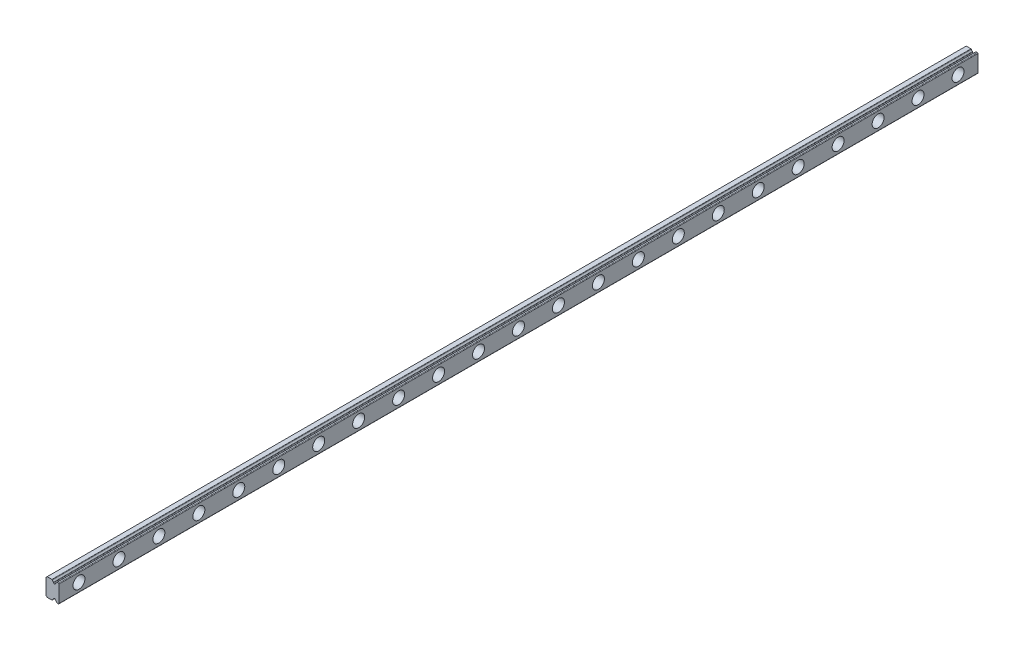
SolidWorks part; units mm, degrees
material "AISI 304"
ref_plane "前视基准面" through (0, 0, 0) normal (0, 0, 1) x (1, 0, 0)
ref_plane "上视基准面" through (0, 0, 0) normal (0, 1, 0) x (1, 0, 0)
ref_plane "右视基准面" through (0, 0, 0) normal (1, 0, 0) x (0, 0, -1)
sketch "草图1" plane through (0, 0, 0) normal (0, 0, 1) x (1, 0, 0)
  line L0 (0, 8.4) -> (0.6, 9)
  line L1 (0.6, 0) -> (2.9423, 0)
  line L2 (0, 0.6) -> (0, 8.4)
  line L3 (0.6, 9) -> (2.9423, 9)
  line L4 (6.5, 0.3) -> (6.5, 8.7)
  line L5 (0, 0.6) -> (0.6, 0)
  line L6 (4.25, 9) -> (4.25, 8) construction
  line L7 (4.25, 9) -> (4.25, 9.3) construction
  line L8 (3.85, 8) -> (3.85, 8.0351)
  line L9 (4.65, 8) -> (4.65, 8.0351)
  line L10 (5.5577, 9) -> (6.2, 9)
  line L11 (6.5, 4.5) -> (0, 4.5) construction
  line L12 (3.85, 8) -> (3.85, 8.0351)
  line L13 (4.65, 8) -> (4.65, 8.0351)
  line L14 (4.25, 0) -> (4.25, -0.3) construction
  line L15 (4.25, 0) -> (4.25, 1) construction
  line L16 (4.65, 1) -> (4.65, 0.9649)
  line L17 (3.85, 1) -> (3.85, 0.9649)
  line L18 (4.65, 1) -> (4.65, 0.9649)
  line L19 (3.85, 1) -> (3.85, 0.9649)
  line L20 (5.5577, 0) -> (6.2, 0)
  arc A0 (3.85, 8) -> (4.65, 8) centre (4.25, 8) ccw
  arc A1 (3.1291, 8.8714) -> (3.7357, 8.2158) centre (4.25, 9.3) ccw
  arc A2 (4.7643, 8.2158) -> (5.3709, 8.8714) centre (4.25, 9.3) ccw
  arc A3 (5.3709, 8.8714) -> (5.5577, 9) centre (5.5577, 8.8) cw
  arc A4 (4.65, 8.0351) -> (4.7643, 8.2158) centre (4.85, 8.0351) cw
  arc A5 (3.85, 8.0351) -> (3.7357, 8.2158) centre (3.65, 8.0351) ccw
  arc A6 (3.1291, 8.8714) -> (2.9423, 9) centre (2.9423, 8.8) ccw
  arc A7 (3.1291, 8.8714) -> (2.9423, 9) centre (2.9423, 8.8) ccw
  arc A8 (5.3709, 8.8714) -> (5.5577, 9) centre (5.5577, 8.8) cw
  arc A9 (4.65, 8.0351) -> (4.7643, 8.2158) centre (4.85, 8.0351) cw
  arc A10 (3.85, 8.0351) -> (3.7357, 8.2158) centre (3.65, 8.0351) ccw
  arc A11 (3.7357, 8.2158) -> (3.1291, 8.8714) centre (4.25, 9.3) cw
  arc A12 (5.3709, 8.8714) -> (4.7643, 8.2158) centre (4.25, 9.3) cw
  arc A13 (5.3709, 0.1286) -> (5.5577, 0) centre (5.5577, 0.2) ccw
  arc A14 (3.1291, 0.1286) -> (2.9423, 0) centre (2.9423, 0.2) cw
  arc A15 (5.3709, 0.1286) -> (4.7643, 0.7842) centre (4.25, -0.3) ccw
  arc A16 (3.7357, 0.7842) -> (3.1291, 0.1286) centre (4.25, -0.3) ccw
  arc A17 (3.85, 0.9649) -> (3.7357, 0.7842) centre (3.65, 0.9649) cw
  arc A18 (4.65, 0.9649) -> (4.7643, 0.7842) centre (4.85, 0.9649) ccw
  arc A19 (3.85, 0.9649) -> (3.7357, 0.7842) centre (3.65, 0.9649) cw
  arc A20 (4.65, 0.9649) -> (4.7643, 0.7842) centre (4.85, 0.9649) ccw
  arc A21 (4.7643, 0.7842) -> (5.3709, 0.1286) centre (4.25, -0.3) cw
  arc A22 (3.1291, 0.1286) -> (3.7357, 0.7842) centre (4.25, -0.3) cw
  arc A23 (3.85, 1) -> (4.65, 1) centre (4.25, 1) cw
  arc A24 (6.2, 0) -> (6.5, 0.3) centre (6.2, 0.3) ccw
  arc A25 (6.2, 9) -> (6.5, 8.7) centre (6.2, 8.7) cw
  point P0 (0, 0)
  point P2 (0, 9)
  point P24 (5.4119, 9)
  point P27 (4.65, 8.1686)
  point P49 (4.65, 0.8314)
  point P50 (5.4119, 0)
  point P53 (6.5, 0)
  dimension "D3" = 1
  dimension "D7" = 0.8
  dimension "D9" = 2.4
  dimension "D10" = 0.2
  dimension "D11" = 0.3
  dimension "D1" = 6.5
  dimension "D2" = 9
  dimension "D4" = 2.25
  dimension "D8" = 0.3
extrude "凸台-拉伸1" add sketch "草图1" along normal blind 400 contours A25 L10 A3 A2 A4 L9 A0 L8 A5 A1 A6 L3 L0 L2 L5 L1 A14 A16 A17 L17 A23 L16 A18 A15 A13 L20 A24 L4
sketch "草图2" plane through (6.5, 0, 0) normal (1, 0, 0) x (0, 0, -1)
  line L0 (-400, 4.5) -> (-390, 4.5) construction
  line L1 (-400, 0.3) -> (-400, 8.7) construction
  line L2 (-390, 4.5) -> (-10, 4.5) construction
  line L3 (-10, 4.5) -> (0, 4.5) construction
  line L4 (0, 0.3) -> (0, 8.7) construction
  line L5 (-10, 4.5) -> (-30, 4.5) construction
  circle A0 centre (-10, 4.5) radius 3
  circle A1 centre (-30, 4.5) radius 3
  circle A2 centre (-50, 4.5) radius 3
  circle A3 centre (-70, 4.5) radius 3
  circle A4 centre (-90, 4.5) radius 3
  circle A5 centre (-110, 4.5) radius 3
  circle A6 centre (-130, 4.5) radius 3
  circle A7 centre (-150, 4.5) radius 3
  circle A8 centre (-170, 4.5) radius 3
  circle A9 centre (-190, 4.5) radius 3
  circle A10 centre (-210, 4.5) radius 3
  circle A11 centre (-230, 4.5) radius 3
  circle A12 centre (-250, 4.5) radius 3
  circle A13 centre (-270, 4.5) radius 3
  circle A14 centre (-290, 4.5) radius 3
  circle A15 centre (-310, 4.5) radius 3
  circle A16 centre (-330, 4.5) radius 3
  circle A17 centre (-350, 4.5) radius 3
  circle A18 centre (-370, 4.5) radius 3
  circle A19 centre (-390, 4.5) radius 3
  circle A20 centre (-410, 4.5) radius 3
  circle A21 centre (-430, 4.5) radius 3
  circle A22 centre (-450, 4.5) radius 3
  circle A23 centre (-470, 4.5) radius 3
  circle A24 centre (-490, 4.5) radius 3
  circle A25 centre (-510, 4.5) radius 3
  circle A26 centre (-530, 4.5) radius 3
  circle A27 centre (-550, 4.5) radius 3
  circle A28 centre (-570, 4.5) radius 3
  circle A29 centre (-590, 4.5) radius 3
  circle A30 centre (-610, 4.5) radius 3
  circle A31 centre (-630, 4.5) radius 3
  circle A32 centre (-650, 4.5) radius 3
  circle A33 centre (-670, 4.5) radius 3
  circle A34 centre (-690, 4.5) radius 3
  circle A35 centre (-710, 4.5) radius 3
  circle A36 centre (-730, 4.5) radius 3
  circle A37 centre (-750, 4.5) radius 3
  circle A38 centre (-770, 4.5) radius 3
  circle A39 centre (-790, 4.5) radius 3
  circle A40 centre (-810, 4.5) radius 3
  circle A41 centre (-830, 4.5) radius 3
  circle A42 centre (-850, 4.5) radius 3
  circle A43 centre (-870, 4.5) radius 3
  circle A44 centre (-890, 4.5) radius 3
  circle A45 centre (-910, 4.5) radius 3
  circle A46 centre (-930, 4.5) radius 3
  circle A47 centre (-950, 4.5) radius 3
  circle A48 centre (-970, 4.5) radius 3
  circle A49 centre (-990, 4.5) radius 3
  circle A50 centre (-1010, 4.5) radius 3
  circle A51 centre (-1030, 4.5) radius 3
  circle A52 centre (-1050, 4.5) radius 3
  circle A53 centre (-1070, 4.5) radius 3
  circle A54 centre (-1090, 4.5) radius 3
  circle A55 centre (-1110, 4.5) radius 3
  circle A56 centre (-1130, 4.5) radius 3
  circle A57 centre (-1150, 4.5) radius 3
  circle A58 centre (-1170, 4.5) radius 3
  circle A59 centre (-1190, 4.5) radius 3
  circle A60 centre (-1210, 4.5) radius 3
  circle A61 centre (-1230, 4.5) radius 3
  circle A62 centre (-1250, 4.5) radius 3
  circle A63 centre (-1270, 4.5) radius 3
  circle A64 centre (-1290, 4.5) radius 3
  circle A65 centre (-1310, 4.5) radius 3
  circle A66 centre (-1330, 4.5) radius 3
  circle A67 centre (-1350, 4.5) radius 3
  circle A68 centre (-1370, 4.5) radius 3
  circle A69 centre (-1390, 4.5) radius 3
  circle A70 centre (-1410, 4.5) radius 3
  circle A71 centre (-1430, 4.5) radius 3
  circle A72 centre (-1450, 4.5) radius 3
  circle A73 centre (-1470, 4.5) radius 3
  circle A74 centre (-1490, 4.5) radius 3
  circle A75 centre (-1510, 4.5) radius 3
  circle A76 centre (-1530, 4.5) radius 3
  circle A77 centre (-1550, 4.5) radius 3
  circle A78 centre (-1570, 4.5) radius 3
  circle A79 centre (-1590, 4.5) radius 3
  circle A80 centre (-1610, 4.5) radius 3
  circle A81 centre (-1630, 4.5) radius 3
  circle A82 centre (-1650, 4.5) radius 3
  circle A83 centre (-1670, 4.5) radius 3
  circle A84 centre (-1690, 4.5) radius 3
  circle A85 centre (-1710, 4.5) radius 3
  circle A86 centre (-1730, 4.5) radius 3
  circle A87 centre (-1750, 4.5) radius 3
  circle A88 centre (-1770, 4.5) radius 3
  circle A89 centre (-1790, 4.5) radius 3
  circle A90 centre (-1810, 4.5) radius 3
  circle A91 centre (-1830, 4.5) radius 3
  circle A92 centre (-1850, 4.5) radius 3
  circle A93 centre (-1870, 4.5) radius 3
  circle A94 centre (-1890, 4.5) radius 3
  circle A95 centre (-1910, 4.5) radius 3
  circle A96 centre (-1930, 4.5) radius 3
  circle A97 centre (-1950, 4.5) radius 3
  circle A98 centre (-1970, 4.5) radius 3
  circle A99 centre (-1990, 4.5) radius 3
  circle A100 centre (-2010, 4.5) radius 3
  circle A101 centre (-2030, 4.5) radius 3
  circle A102 centre (-2050, 4.5) radius 3
  circle A103 centre (-2070, 4.5) radius 3
  circle A104 centre (-2090, 4.5) radius 3
  circle A105 centre (-2110, 4.5) radius 3
  circle A106 centre (-2130, 4.5) radius 3
  circle A107 centre (-2150, 4.5) radius 3
  circle A108 centre (-2170, 4.5) radius 3
  circle A109 centre (-2190, 4.5) radius 3
  circle A110 centre (-2210, 4.5) radius 3
  circle A111 centre (-2230, 4.5) radius 3
  circle A112 centre (-2250, 4.5) radius 3
  circle A113 centre (-2270, 4.5) radius 3
  circle A114 centre (-2290, 4.5) radius 3
  circle A115 centre (-2310, 4.5) radius 3
  circle A116 centre (-2330, 4.5) radius 3
  circle A117 centre (-2350, 4.5) radius 3
  circle A118 centre (-2370, 4.5) radius 3
  circle A119 centre (-2390, 4.5) radius 3
  circle A120 centre (-2410, 4.5) radius 3
  circle A121 centre (-2430, 4.5) radius 3
  circle A122 centre (-2450, 4.5) radius 3
  circle A123 centre (-2470, 4.5) radius 3
  dimension "D2" = 6
  dimension "D1" = 10
  dimension "D4" = 20
  dimension "D3" = 25
  dimension "D5" = 100
extrude "切除-拉伸1" cut sketch "草图2" against normal blind 4.5
sketch "草图3" plane through (2, 0, 0) normal (1, 0, 0) x (0, 0, -1)
  line L0 (-10, 4.5) -> (-30, 4.5) construction
  circle A0 centre (-10, 4.5) radius 1.75
  circle A1 centre (-30, 4.5) radius 1.75
  circle A2 centre (-50, 4.5) radius 1.75
  circle A3 centre (-70, 4.5) radius 1.75
  circle A4 centre (-90, 4.5) radius 1.75
  circle A5 centre (-110, 4.5) radius 1.75
  circle A6 centre (-130, 4.5) radius 1.75
  circle A7 centre (-150, 4.5) radius 1.75
  circle A8 centre (-170, 4.5) radius 1.75
  circle A9 centre (-190, 4.5) radius 1.75
  circle A10 centre (-210, 4.5) radius 1.75
  circle A11 centre (-230, 4.5) radius 1.75
  circle A12 centre (-250, 4.5) radius 1.75
  circle A13 centre (-270, 4.5) radius 1.75
  circle A14 centre (-290, 4.5) radius 1.75
  circle A15 centre (-310, 4.5) radius 1.75
  circle A16 centre (-330, 4.5) radius 1.75
  circle A17 centre (-350, 4.5) radius 1.75
  circle A18 centre (-370, 4.5) radius 1.75
  circle A19 centre (-390, 4.5) radius 1.75
  circle A20 centre (-410, 4.5) radius 1.75
  circle A21 centre (-430, 4.5) radius 1.75
  circle A22 centre (-450, 4.5) radius 1.75
  circle A23 centre (-470, 4.5) radius 1.75
  circle A24 centre (-490, 4.5) radius 1.75
  circle A25 centre (-510, 4.5) radius 1.75
  circle A26 centre (-530, 4.5) radius 1.75
  circle A27 centre (-550, 4.5) radius 1.75
  circle A28 centre (-570, 4.5) radius 1.75
  circle A29 centre (-590, 4.5) radius 1.75
  circle A30 centre (-610, 4.5) radius 1.75
  circle A31 centre (-630, 4.5) radius 1.75
  circle A32 centre (-650, 4.5) radius 1.75
  circle A33 centre (-670, 4.5) radius 1.75
  circle A34 centre (-690, 4.5) radius 1.75
  circle A35 centre (-710, 4.5) radius 1.75
  circle A36 centre (-730, 4.5) radius 1.75
  circle A37 centre (-750, 4.5) radius 1.75
  circle A38 centre (-770, 4.5) radius 1.75
  circle A39 centre (-790, 4.5) radius 1.75
  circle A40 centre (-810, 4.5) radius 1.75
  circle A41 centre (-830, 4.5) radius 1.75
  circle A42 centre (-850, 4.5) radius 1.75
  circle A43 centre (-870, 4.5) radius 1.75
  circle A44 centre (-890, 4.5) radius 1.75
  circle A45 centre (-910, 4.5) radius 1.75
  circle A46 centre (-930, 4.5) radius 1.75
  circle A47 centre (-950, 4.5) radius 1.75
  circle A48 centre (-970, 4.5) radius 1.75
  circle A49 centre (-990, 4.5) radius 1.75
  circle A50 centre (-1010, 4.5) radius 1.75
  circle A51 centre (-1030, 4.5) radius 1.75
  circle A52 centre (-1050, 4.5) radius 1.75
  circle A53 centre (-1070, 4.5) radius 1.75
  dimension "D1" = 3.5
  dimension "D3" = 20
  dimension "D2" = 25
  dimension "D4" = 30
extrude "切除-拉伸2" cut sketch "草图3" against normal through all
sketch "草图4" plane through (0, 0, 400) normal (0, 0, 1) x (1, 0, 0)
  line L12 (6.2, 9) -> (5.5577, 9)
  line L13 (4.65, 8.0351) -> (4.65, 8)
  line L14 (3.85, 8) -> (3.85, 8.0351)
  line L15 (2.9423, 9) -> (0.6, 9)
  line L16 (0.6, 9) -> (0, 8.4)
  line L17 (0, 8.4) -> (0, 0.6)
  line L18 (0, 0.6) -> (0.6, 0)
  line L19 (0.6, 0) -> (2.9423, 0)
  line L20 (3.85, 0.9649) -> (3.85, 1)
  line L21 (4.65, 1) -> (4.65, 0.9649)
  line L22 (5.5577, 0) -> (6.2, 0)
  line L23 (6.5, 0.3) -> (6.5, 8.7)
  line L24 (6.2, 9) -> (5.5577, 9)
  line L25 (4.65, 8.0351) -> (4.65, 8)
  line L26 (3.85, 8) -> (3.85, 8.0351)
  line L27 (2.9423, 9) -> (0.6, 9)
  line L28 (0.6, 9) -> (0, 8.4)
  line L29 (0, 8.4) -> (0, 0.6)
  line L30 (0, 0.6) -> (0.6, 0)
  line L31 (0.6, 0) -> (2.9423, 0)
  line L32 (3.85, 0.9649) -> (3.85, 1)
  line L33 (4.65, 1) -> (4.65, 0.9649)
  line L34 (5.5577, 0) -> (6.2, 0)
  line L35 (6.5, 0.3) -> (6.5, 8.7)
  arc A16 (6.5, 8.7) -> (6.2, 9) centre (6.2, 8.7) ccw
  arc A17 (5.5577, 9) -> (5.3709, 8.8714) centre (5.5577, 8.8) ccw
  arc A18 (4.7643, 8.2158) -> (5.3709, 8.8714) centre (4.25, 9.3) ccw
  arc A19 (4.7643, 8.2158) -> (4.65, 8.0351) centre (4.85, 8.0351) ccw
  arc A20 (3.85, 8) -> (4.65, 8) centre (4.25, 8) ccw
  arc A21 (3.85, 8.0351) -> (3.7357, 8.2158) centre (3.65, 8.0351) ccw
  arc A22 (3.1291, 8.8714) -> (3.7357, 8.2158) centre (4.25, 9.3) ccw
  arc A23 (3.1291, 8.8714) -> (2.9423, 9) centre (2.9423, 8.8) ccw
  arc A24 (2.9423, 0) -> (3.1291, 0.1286) centre (2.9423, 0.2) ccw
  arc A25 (3.7357, 0.7842) -> (3.1291, 0.1286) centre (4.25, -0.3) ccw
  arc A26 (3.7357, 0.7842) -> (3.85, 0.9649) centre (3.65, 0.9649) ccw
  arc A27 (4.65, 1) -> (3.85, 1) centre (4.25, 1) ccw
  arc A28 (4.65, 0.9649) -> (4.7643, 0.7842) centre (4.85, 0.9649) ccw
  arc A29 (5.3709, 0.1286) -> (4.7643, 0.7842) centre (4.25, -0.3) ccw
  arc A30 (5.3709, 0.1286) -> (5.5577, 0) centre (5.5577, 0.2) ccw
  arc A31 (6.2, 0) -> (6.5, 0.3) centre (6.2, 0.3) ccw
  arc A32 (6.5, 8.7) -> (6.2, 9) centre (6.2, 8.7) ccw
  arc A33 (5.5577, 9) -> (5.3709, 8.8714) centre (5.5577, 8.8) ccw
  arc A34 (4.7643, 8.2158) -> (5.3709, 8.8714) centre (4.25, 9.3) ccw
  arc A35 (4.7643, 8.2158) -> (4.65, 8.0351) centre (4.85, 8.0351) ccw
  arc A36 (3.85, 8) -> (4.65, 8) centre (4.25, 8) ccw
  arc A37 (3.85, 8.0351) -> (3.7357, 8.2158) centre (3.65, 8.0351) ccw
  arc A38 (3.1291, 8.8714) -> (3.7357, 8.2158) centre (4.25, 9.3) ccw
  arc A39 (3.1291, 8.8714) -> (2.9423, 9) centre (2.9423, 8.8) ccw
  arc A40 (2.9423, 0) -> (3.1291, 0.1286) centre (2.9423, 0.2) ccw
  arc A41 (3.7357, 0.7842) -> (3.1291, 0.1286) centre (4.25, -0.3) ccw
  arc A42 (3.7357, 0.7842) -> (3.85, 0.9649) centre (3.65, 0.9649) ccw
  arc A43 (4.65, 1) -> (3.85, 1) centre (4.25, 1) ccw
  arc A44 (4.65, 0.9649) -> (4.7643, 0.7842) centre (4.85, 0.9649) ccw
  arc A45 (5.3709, 0.1286) -> (4.7643, 0.7842) centre (4.25, -0.3) ccw
  arc A46 (5.3709, 0.1286) -> (5.5577, 0) centre (5.5577, 0.2) ccw
  arc A47 (6.2, 0) -> (6.5, 0.3) centre (6.2, 0.3) ccw
  dimension "D1" = 0
sketch "草图5" plane through (0, 0, 0) normal (0, 0, -1) x (-1, 0, 0)
  line L12 (-6.5, 8.7) -> (-6.5, 0.3)
  line L13 (-6.2, 0) -> (-5.5577, 0)
  line L14 (-4.65, 0.9649) -> (-4.65, 1)
  line L15 (-3.85, 1) -> (-3.85, 0.9649)
  line L16 (-2.9423, 0) -> (-0.6, 0)
  line L17 (-0.6, 0) -> (0, 0.6)
  line L18 (0, 0.6) -> (0, 8.4)
  line L19 (0, 8.4) -> (-0.6, 9)
  line L20 (-0.6, 9) -> (-2.9423, 9)
  line L21 (-3.85, 8.0351) -> (-3.85, 8)
  line L22 (-4.65, 8) -> (-4.65, 8.0351)
  line L23 (-5.5577, 9) -> (-6.2, 9)
  line L24 (-6.5, 8.7) -> (-6.5, 0.3)
  line L25 (-6.2, 0) -> (-5.5577, 0)
  line L26 (-4.65, 0.9649) -> (-4.65, 1)
  line L27 (-3.85, 1) -> (-3.85, 0.9649)
  line L28 (-2.9423, 0) -> (-0.6, 0)
  line L29 (-0.6, 0) -> (0, 0.6)
  line L30 (0, 0.6) -> (0, 8.4)
  line L31 (0, 8.4) -> (-0.6, 9)
  line L32 (-0.6, 9) -> (-2.9423, 9)
  line L33 (-3.85, 8.0351) -> (-3.85, 8)
  line L34 (-4.65, 8) -> (-4.65, 8.0351)
  line L35 (-5.5577, 9) -> (-6.2, 9)
  arc A16 (-6.2, 9) -> (-6.5, 8.7) centre (-6.2, 8.7) ccw
  arc A17 (-6.5, 0.3) -> (-6.2, 0) centre (-6.2, 0.3) ccw
  arc A18 (-5.5577, 0) -> (-5.3709, 0.1286) centre (-5.5577, 0.2) ccw
  arc A19 (-4.7643, 0.7842) -> (-5.3709, 0.1286) centre (-4.25, -0.3) ccw
  arc A20 (-4.7643, 0.7842) -> (-4.65, 0.9649) centre (-4.85, 0.9649) ccw
  arc A21 (-3.85, 1) -> (-4.65, 1) centre (-4.25, 1) ccw
  arc A22 (-3.85, 0.9649) -> (-3.7357, 0.7842) centre (-3.65, 0.9649) ccw
  arc A23 (-3.1291, 0.1286) -> (-3.7357, 0.7842) centre (-4.25, -0.3) ccw
  arc A24 (-3.1291, 0.1286) -> (-2.9423, 0) centre (-2.9423, 0.2) ccw
  arc A25 (-2.9423, 9) -> (-3.1291, 8.8714) centre (-2.9423, 8.8) ccw
  arc A26 (-3.7357, 8.2158) -> (-3.1291, 8.8714) centre (-4.25, 9.3) ccw
  arc A27 (-3.7357, 8.2158) -> (-3.85, 8.0351) centre (-3.65, 8.0351) ccw
  arc A28 (-4.65, 8) -> (-3.85, 8) centre (-4.25, 8) ccw
  arc A29 (-4.65, 8.0351) -> (-4.7643, 8.2158) centre (-4.85, 8.0351) ccw
  arc A30 (-5.3709, 8.8714) -> (-4.7643, 8.2158) centre (-4.25, 9.3) ccw
  arc A31 (-5.3709, 8.8714) -> (-5.5577, 9) centre (-5.5577, 8.8) ccw
  arc A32 (-6.2, 9) -> (-6.5, 8.7) centre (-6.2, 8.7) ccw
  arc A33 (-6.5, 0.3) -> (-6.2, 0) centre (-6.2, 0.3) ccw
  arc A34 (-5.5577, 0) -> (-5.3709, 0.1286) centre (-5.5577, 0.2) ccw
  arc A35 (-4.7643, 0.7842) -> (-5.3709, 0.1286) centre (-4.25, -0.3) ccw
  arc A36 (-4.7643, 0.7842) -> (-4.65, 0.9649) centre (-4.85, 0.9649) ccw
  arc A37 (-3.85, 1) -> (-4.65, 1) centre (-4.25, 1) ccw
  arc A38 (-3.85, 0.9649) -> (-3.7357, 0.7842) centre (-3.65, 0.9649) ccw
  arc A39 (-3.1291, 0.1286) -> (-3.7357, 0.7842) centre (-4.25, -0.3) ccw
  arc A40 (-3.1291, 0.1286) -> (-2.9423, 0) centre (-2.9423, 0.2) ccw
  arc A41 (-2.9423, 9) -> (-3.1291, 8.8714) centre (-2.9423, 8.8) ccw
  arc A42 (-3.7357, 8.2158) -> (-3.1291, 8.8714) centre (-4.25, 9.3) ccw
  arc A43 (-3.7357, 8.2158) -> (-3.85, 8.0351) centre (-3.65, 8.0351) ccw
  arc A44 (-4.65, 8) -> (-3.85, 8) centre (-4.25, 8) ccw
  arc A45 (-4.65, 8.0351) -> (-4.7643, 8.2158) centre (-4.85, 8.0351) ccw
  arc A46 (-5.3709, 8.8714) -> (-4.7643, 8.2158) centre (-4.25, 9.3) ccw
  arc A47 (-5.3709, 8.8714) -> (-5.5577, 9) centre (-5.5577, 8.8) ccw
  dimension "D1" = 0
extrude "切除-拉伸4" cut sketch "草图5" against normal blind 80
sketch "草图6" plane through (0, 0, 400) normal (0, 0, 1) x (1, 0, 0)
  line L12 (6.2, 9) -> (5.5577, 9)
  line L13 (4.65, 8.0351) -> (4.65, 8)
  line L14 (3.85, 8) -> (3.85, 8.0351)
  line L15 (2.9423, 9) -> (0.6, 9)
  line L16 (0.6, 9) -> (0, 8.4)
  line L17 (0, 8.4) -> (0, 0.6)
  line L18 (0, 0.6) -> (0.6, 0)
  line L19 (0.6, 0) -> (2.9423, 0)
  line L20 (3.85, 0.9649) -> (3.85, 1)
  line L21 (4.65, 1) -> (4.65, 0.9649)
  line L22 (5.5577, 0) -> (6.2, 0)
  line L23 (6.5, 0.3) -> (6.5, 8.7)
  line L24 (6.2, 9) -> (5.5577, 9)
  line L25 (4.65, 8.0351) -> (4.65, 8)
  line L26 (3.85, 8) -> (3.85, 8.0351)
  line L27 (2.9423, 9) -> (0.6, 9)
  line L28 (0.6, 9) -> (0, 8.4)
  line L29 (0, 8.4) -> (0, 0.6)
  line L30 (0, 0.6) -> (0.6, 0)
  line L31 (0.6, 0) -> (2.9423, 0)
  line L32 (3.85, 0.9649) -> (3.85, 1)
  line L33 (4.65, 1) -> (4.65, 0.9649)
  line L34 (5.5577, 0) -> (6.2, 0)
  line L35 (6.5, 0.3) -> (6.5, 8.7)
  arc A16 (6.5, 8.7) -> (6.2, 9) centre (6.2, 8.7) ccw
  arc A17 (5.5577, 9) -> (5.3709, 8.8714) centre (5.5577, 8.8) ccw
  arc A18 (4.7643, 8.2158) -> (5.3709, 8.8714) centre (4.25, 9.3) ccw
  arc A19 (4.7643, 8.2158) -> (4.65, 8.0351) centre (4.85, 8.0351) ccw
  arc A20 (3.85, 8) -> (4.65, 8) centre (4.25, 8) ccw
  arc A21 (3.85, 8.0351) -> (3.7357, 8.2158) centre (3.65, 8.0351) ccw
  arc A22 (3.1291, 8.8714) -> (3.7357, 8.2158) centre (4.25, 9.3) ccw
  arc A23 (3.1291, 8.8714) -> (2.9423, 9) centre (2.9423, 8.8) ccw
  arc A24 (2.9423, 0) -> (3.1291, 0.1286) centre (2.9423, 0.2) ccw
  arc A25 (3.7357, 0.7842) -> (3.1291, 0.1286) centre (4.25, -0.3) ccw
  arc A26 (3.7357, 0.7842) -> (3.85, 0.9649) centre (3.65, 0.9649) ccw
  arc A27 (4.65, 1) -> (3.85, 1) centre (4.25, 1) ccw
  arc A28 (4.65, 0.9649) -> (4.7643, 0.7842) centre (4.85, 0.9649) ccw
  arc A29 (5.3709, 0.1286) -> (4.7643, 0.7842) centre (4.25, -0.3) ccw
  arc A30 (5.3709, 0.1286) -> (5.5577, 0) centre (5.5577, 0.2) ccw
  arc A31 (6.2, 0) -> (6.5, 0.3) centre (6.2, 0.3) ccw
  arc A32 (6.5, 8.7) -> (6.2, 9) centre (6.2, 8.7) ccw
  arc A33 (5.5577, 9) -> (5.3709, 8.8714) centre (5.5577, 8.8) ccw
  arc A34 (4.7643, 8.2158) -> (5.3709, 8.8714) centre (4.25, 9.3) ccw
  arc A35 (4.7643, 8.2158) -> (4.65, 8.0351) centre (4.85, 8.0351) ccw
  arc A36 (3.85, 8) -> (4.65, 8) centre (4.25, 8) ccw
  arc A37 (3.85, 8.0351) -> (3.7357, 8.2158) centre (3.65, 8.0351) ccw
  arc A38 (3.1291, 8.8714) -> (3.7357, 8.2158) centre (4.25, 9.3) ccw
  arc A39 (3.1291, 8.8714) -> (2.9423, 9) centre (2.9423, 8.8) ccw
  arc A40 (2.9423, 0) -> (3.1291, 0.1286) centre (2.9423, 0.2) ccw
  arc A41 (3.7357, 0.7842) -> (3.1291, 0.1286) centre (4.25, -0.3) ccw
  arc A42 (3.7357, 0.7842) -> (3.85, 0.9649) centre (3.65, 0.9649) ccw
  arc A43 (4.65, 1) -> (3.85, 1) centre (4.25, 1) ccw
  arc A44 (4.65, 0.9649) -> (4.7643, 0.7842) centre (4.85, 0.9649) ccw
  arc A45 (5.3709, 0.1286) -> (4.7643, 0.7842) centre (4.25, -0.3) ccw
  arc A46 (5.3709, 0.1286) -> (5.5577, 0) centre (5.5577, 0.2) ccw
  arc A47 (6.2, 0) -> (6.5, 0.3) centre (6.2, 0.3) ccw
  dimension "D1" = 0
extrude "凸台-拉伸2" add sketch "草图6" along normal blind 200
sketch "草图7" plane through (0, 0, 0) normal (-1, 0, 0) x (0, 0, 1)
  circle A0 centre (390, 4.5) radius 1.75 construction
  circle A1 centre (390, 4.5) radius 1.75
  circle A2 centre (410, 4.5) radius 1.75
  circle A3 centre (430, 4.5) radius 1.75
  circle A4 centre (450, 4.5) radius 1.75
  circle A5 centre (470, 4.5) radius 1.75
  circle A6 centre (490, 4.5) radius 1.75
  circle A7 centre (510, 4.5) radius 1.75
  circle A8 centre (530, 4.5) radius 1.75
  circle A9 centre (550, 4.5) radius 1.75
  circle A10 centre (570, 4.5) radius 1.75
  circle A11 centre (590, 4.5) radius 1.75
  dimension "D1" = 11
extrude "切除-拉伸5" cut sketch "草图7" against normal blind 100
sketch "草图8" plane through (6.5, 0, 0) normal (1, 0, 0) x (0, 0, -1)
  circle A0 centre (-390, 4.5) radius 3 construction
  circle A1 centre (-390, 4.5) radius 3
  circle A2 centre (-410, 4.5) radius 3
  circle A3 centre (-430, 4.5) radius 3
  circle A4 centre (-450, 4.5) radius 3
  circle A5 centre (-470, 4.5) radius 3
  circle A6 centre (-490, 4.5) radius 3
  circle A7 centre (-510, 4.5) radius 3
  circle A8 centre (-530, 4.5) radius 3
  circle A9 centre (-550, 4.5) radius 3
  circle A10 centre (-570, 4.5) radius 3
  circle A11 centre (-590, 4.5) radius 3
  dimension "D1" = 11
extrude "切除-拉伸6" cut sketch "草图8" against normal blind 4.5
sketch "草图10" plane through (0, 0, 80) normal (0, 0, -1) x (-1, 0, 0)
  line L12 (-6.5, 8.7) -> (-6.5, 0.3)
  line L13 (-6.2, 0) -> (-5.5577, 0)
  line L14 (-4.65, 0.9649) -> (-4.65, 1)
  line L15 (-3.85, 1) -> (-3.85, 0.9649)
  line L16 (-2.9423, 0) -> (-0.6, 0)
  line L17 (-0.6, 0) -> (0, 0.6)
  line L18 (0, 0.6) -> (0, 8.4)
  line L19 (0, 8.4) -> (-0.6, 9)
  line L20 (-0.6, 9) -> (-2.9423, 9)
  line L21 (-3.85, 8.0351) -> (-3.85, 8)
  line L22 (-4.65, 8) -> (-4.65, 8.0351)
  line L23 (-5.5577, 9) -> (-6.2, 9)
  line L24 (-6.5, 8.7) -> (-6.5, 0.3)
  line L25 (-6.2, 0) -> (-5.5577, 0)
  line L26 (-4.65, 0.9649) -> (-4.65, 1)
  line L27 (-3.85, 1) -> (-3.85, 0.9649)
  line L28 (-2.9423, 0) -> (-0.6, 0)
  line L29 (-0.6, 0) -> (0, 0.6)
  line L30 (0, 0.6) -> (0, 8.4)
  line L31 (0, 8.4) -> (-0.6, 9)
  line L32 (-0.6, 9) -> (-2.9423, 9)
  line L33 (-3.85, 8.0351) -> (-3.85, 8)
  line L34 (-4.65, 8) -> (-4.65, 8.0351)
  line L35 (-5.5577, 9) -> (-6.2, 9)
  arc A16 (-6.2, 9) -> (-6.5, 8.7) centre (-6.2, 8.7) ccw
  arc A17 (-6.5, 0.3) -> (-6.2, 0) centre (-6.2, 0.3) ccw
  arc A18 (-5.5577, 0) -> (-5.3709, 0.1286) centre (-5.5577, 0.2) ccw
  arc A19 (-4.7643, 0.7842) -> (-5.3709, 0.1286) centre (-4.25, -0.3) ccw
  arc A20 (-4.7643, 0.7842) -> (-4.65, 0.9649) centre (-4.85, 0.9649) ccw
  arc A21 (-3.85, 1) -> (-4.65, 1) centre (-4.25, 1) ccw
  arc A22 (-3.85, 0.9649) -> (-3.7357, 0.7842) centre (-3.65, 0.9649) ccw
  arc A23 (-3.1291, 0.1286) -> (-3.7357, 0.7842) centre (-4.25, -0.3) ccw
  arc A24 (-3.1291, 0.1286) -> (-2.9423, 0) centre (-2.9423, 0.2) ccw
  arc A25 (-2.9423, 9) -> (-3.1291, 8.8714) centre (-2.9423, 8.8) ccw
  arc A26 (-3.7357, 8.2158) -> (-3.1291, 8.8714) centre (-4.25, 9.3) ccw
  arc A27 (-3.7357, 8.2158) -> (-3.85, 8.0351) centre (-3.65, 8.0351) ccw
  arc A28 (-4.65, 8) -> (-3.85, 8) centre (-4.25, 8) ccw
  arc A29 (-4.65, 8.0351) -> (-4.7643, 8.2158) centre (-4.85, 8.0351) ccw
  arc A30 (-5.3709, 8.8714) -> (-4.7643, 8.2158) centre (-4.25, 9.3) ccw
  arc A31 (-5.3709, 8.8714) -> (-5.5577, 9) centre (-5.5577, 8.8) ccw
  arc A32 (-6.2, 9) -> (-6.5, 8.7) centre (-6.2, 8.7) ccw
  arc A33 (-6.5, 0.3) -> (-6.2, 0) centre (-6.2, 0.3) ccw
  arc A34 (-5.5577, 0) -> (-5.3709, 0.1286) centre (-5.5577, 0.2) ccw
  arc A35 (-4.7643, 0.7842) -> (-5.3709, 0.1286) centre (-4.25, -0.3) ccw
  arc A36 (-4.7643, 0.7842) -> (-4.65, 0.9649) centre (-4.85, 0.9649) ccw
  arc A37 (-3.85, 1) -> (-4.65, 1) centre (-4.25, 1) ccw
  arc A38 (-3.85, 0.9649) -> (-3.7357, 0.7842) centre (-3.65, 0.9649) ccw
  arc A39 (-3.1291, 0.1286) -> (-3.7357, 0.7842) centre (-4.25, -0.3) ccw
  arc A40 (-3.1291, 0.1286) -> (-2.9423, 0) centre (-2.9423, 0.2) ccw
  arc A41 (-2.9423, 9) -> (-3.1291, 8.8714) centre (-2.9423, 8.8) ccw
  arc A42 (-3.7357, 8.2158) -> (-3.1291, 8.8714) centre (-4.25, 9.3) ccw
  arc A43 (-3.7357, 8.2158) -> (-3.85, 8.0351) centre (-3.65, 8.0351) ccw
  arc A44 (-4.65, 8) -> (-3.85, 8) centre (-4.25, 8) ccw
  arc A45 (-4.65, 8.0351) -> (-4.7643, 8.2158) centre (-4.85, 8.0351) ccw
  arc A46 (-5.3709, 8.8714) -> (-4.7643, 8.2158) centre (-4.25, 9.3) ccw
  arc A47 (-5.3709, 8.8714) -> (-5.5577, 9) centre (-5.5577, 8.8) ccw
  dimension "D1" = 0
extrude "切除-拉伸10" cut sketch "草图10" against normal blind 60
